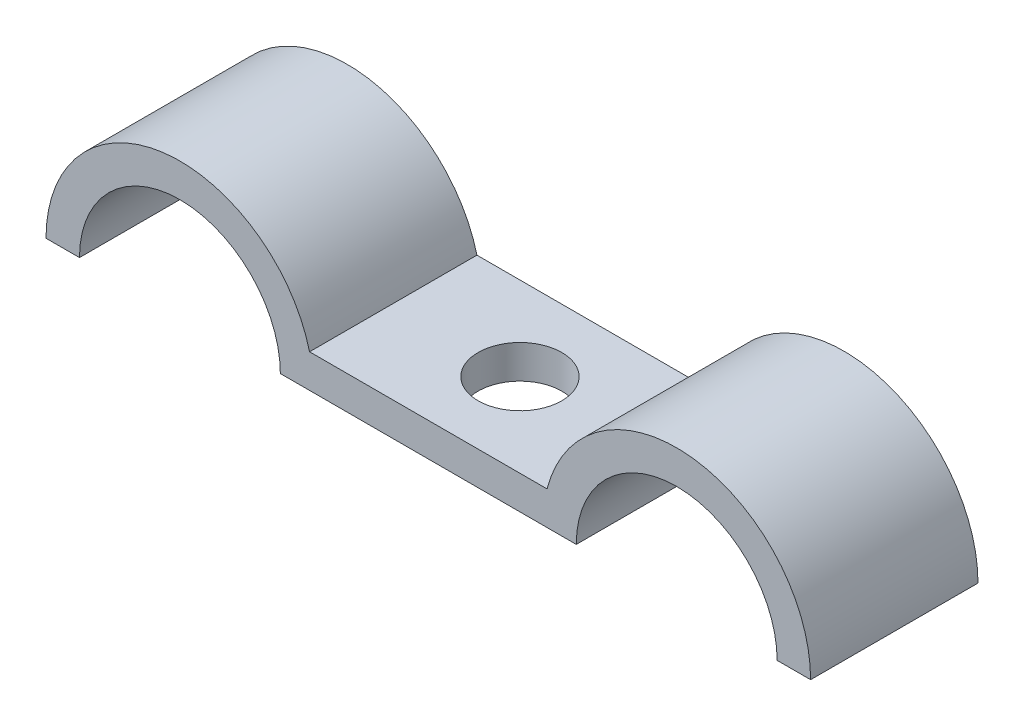
SolidWorks part; units mm, degrees
material "1.5714 (16NiCr4)"
ref_plane "Ön Düzlem" through (0, 0, 0) normal (0, 0, 1) x (1, 0, 0)
ref_plane "Üst Düzlem" through (0, 0, 0) normal (0, 1, 0) x (1, 0, 0)
ref_plane "Sağ Düzlem" through (0, 0, 0) normal (1, 0, 0) x (0, 0, -1)
sketch "Çizim1" plane through (0, 0, 0) normal (0, 0, 1) x (1, 0, 0)
  line L0 (0, 0) -> (17.68, 0)
  line L2 (15.934, 2) -> (1.746, 2)
  line L6 (-12, 0) -> (-14, 0)
  line L7 (29.68, 0) -> (31.68, 0)
  arc A0 (0, 0) -> (-12, 0) centre (-6, 0) ccw
  arc A1 (1.746, 2) -> (-14, 0) centre (-6, 0) ccw
  arc A2 (29.68, 0) -> (17.68, 0) centre (23.68, 0) ccw
  arc A3 (31.68, 0) -> (15.934, 2) centre (23.68, 0) ccw
extrude "Yükseklik-Ekstrüzyon1" add sketch "Çizim1" along normal blind 10
sketch "Çizim2" plane through (0, 2, 0) normal (0, 1, 0) x (1, 0, 0)
  circle A0 centre (9.316, -5) radius 2.5
extrude "Kes-Ekstrüzyon1" cut sketch "Çizim2" against normal blind 5 and the other way blind 10
